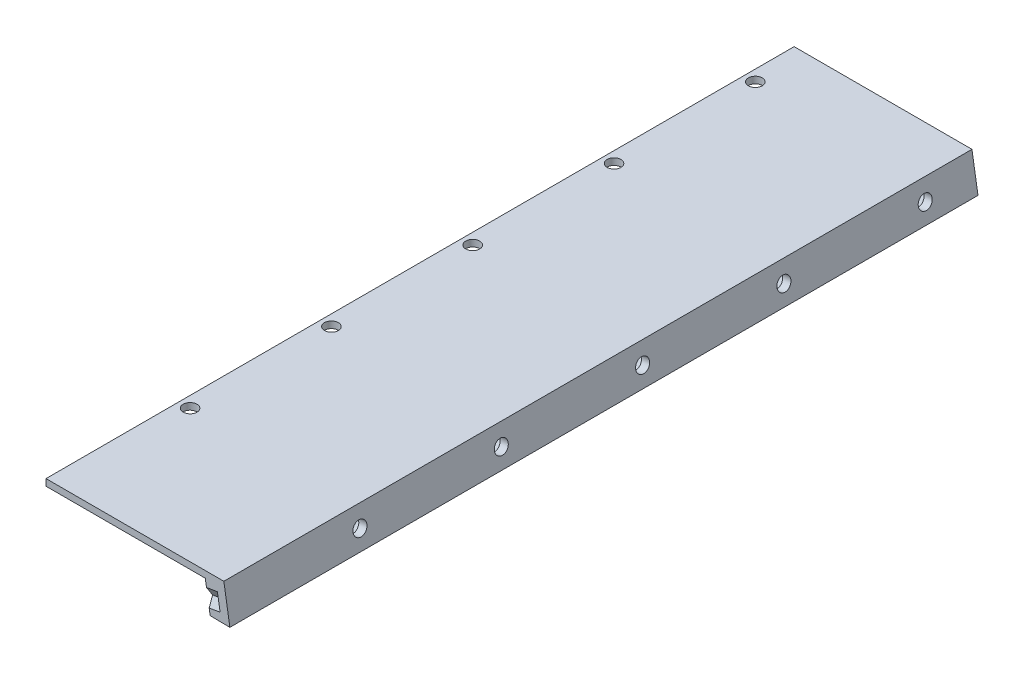
SolidWorks part; units mm, degrees
ref_plane "Front Plane" through (0, 0, 0) normal (0, 0, 1) x (1, 0, 0)
ref_plane "Top Plane" through (0, 0, 0) normal (0, 1, 0) x (1, 0, 0)
ref_plane "Right Plane" through (0, 0, 0) normal (1, 0, 0) x (0, 0, -1)
sketch "Sketch1" plane through (0, 0, 0) normal (0, 0, 1) x (1, 0, 0)
  line L0 (0, 0) -> (32.09, 0)
  line L1 (32.09, 0) -> (33.1785, -6.6617)
  line L2 (0, -1.2) -> (28.7397, -1.2)
  line L3 (28.7397, -1.2) -> (29.6248, -6.617)
  line L4 (0, 0) -> (0, -1.2)
  line L5 (33.1785, -6.6617) -> (29.6248, -6.617)
  dimension "D1" = 1.2
  dimension "D2" = 3.5
  dimension "D3" = 6.75
  dimension "D4" = 80
  dimension "D5" = 99.28
  dimension "D6" = 32.09
extrude "Boss-Extrude1" add sketch "Sketch1" along normal blind 171
sketch "Sketch2" plane through (0, 0, 0) normal (0, 1, 0) x (1, 0, 0)
  line L0 (32.09, 0) -> (0, 0) construction
  line L1 (0, -171) -> (0, 0) construction
  circle A0 centre (2, -9) radius 1.25
  dimension "D1" = 9
  dimension "D2" = 2
  dimension "D3" = 2.5
extrude "Cut-Extrude1" cut sketch "Sketch2" against normal blind 50 contours A0
sketch "Sketch3" plane through (31.2555, 5.1071, 0) normal (0.9869, 0.1613, 0) x (0, 0, -1)
  line L0 (0, -11.9248) -> (0, -5.1748) construction
  line L1 (-171, -11.9248) -> (0, -11.9248) construction
  circle A0 centre (-9, -8.6748) radius 1.25
  dimension "D1" = 9
  dimension "D2" = 2.5
  dimension "D3" = 3.25
extrude "Cut-Extrude2" cut sketch "Sketch3" against normal blind 50 contours A0
sketch "Sketch4" plane through (27.8013, 4.5427, 0) normal (-0.9869, -0.1613, 0) x (0, 0, 1)
  line L1 (7.8164, -6.6248) -> (6.6329, -8.6748)
  line L2 (6.6329, -8.6748) -> (7.8164, -10.7248)
  line L3 (7.8164, -10.7248) -> (10.1836, -10.7248)
  line L4 (10.1836, -10.7248) -> (11.3671, -8.6748)
  line L5 (11.3671, -8.6748) -> (10.1836, -6.6248)
  line L6 (10.1836, -6.6248) -> (7.8164, -6.6248)
  circle A0 centre (9, -8.6748) radius 2.05 construction
  dimension "D1" = 4.1
extrude "Cut-Extrude3" cut sketch "Sketch4" against normal blind 2
pattern_linear "LPattern1" count 7 spacing 25.5 along (0, 0, 1) of "Cut-Extrude1", "Cut-Extrude3", "Cut-Extrude2"
sketch "Sketch5" plane through (0, 0, 171) normal (0, 0, 1) x (1, 0, 0)
  line L1 (-11.4923, -17.8333) -> (46.9305, -17.8333)
  line L2 (-11.4923, -17.8333) -> (-11.4923, 14.4437)
  line L3 (-11.4923, 14.4437) -> (46.9305, 14.4437)
  line L4 (46.9305, -17.8333) -> (46.9305, 14.4437)
extrude "Cut-Extrude4" cut sketch "Sketch5" against normal blind 36
